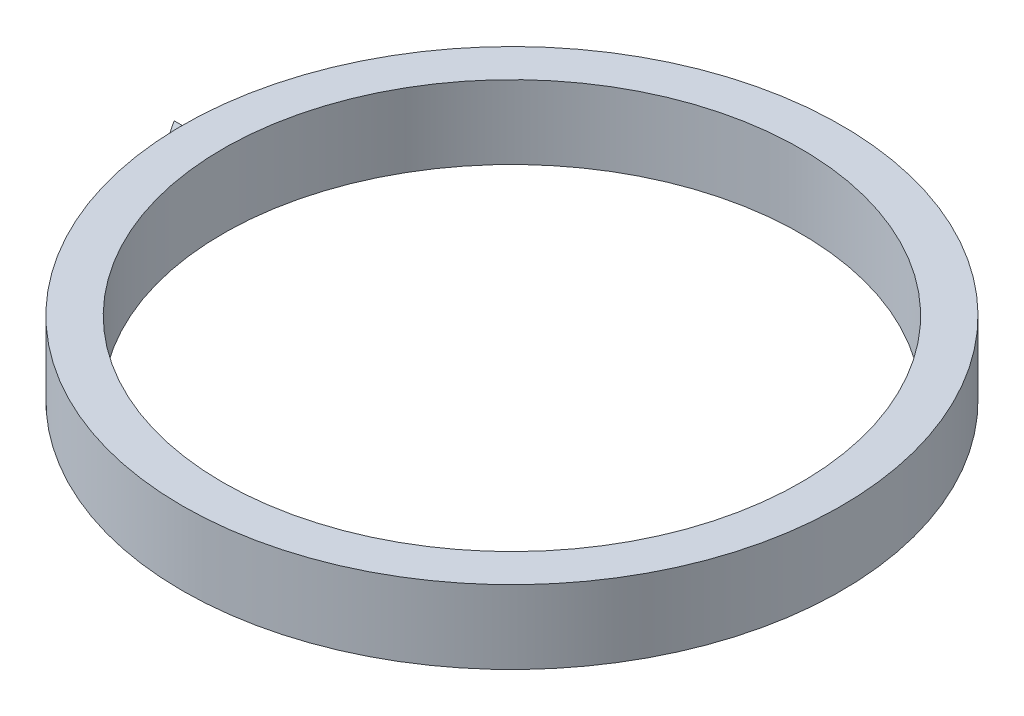
SolidWorks part; units mm, degrees
ref_plane "Front Plane" through (0, 0, 0) normal (0, 0, 1) x (1, 0, 0)
ref_plane "Top Plane" through (0, 0, 0) normal (0, 1, 0) x (1, 0, 0)
ref_plane "Right Plane" through (0, 0, 0) normal (1, 0, 0) x (0, 0, -1)
sketch "Sketch1" plane through (0, 0, 0) normal (0, 1, 0) x (1, 0, 0)
  circle A0 centre (0, 0) radius 19.5
  circle A1 centre (0, 0) radius 17.1
  dimension "D1" = 39
  dimension "D2" = 34.2
extrude "Boss-Extrude1" add sketch "Sketch1" along normal blind 4.3478
ref_plane "Plane1" through (-19.5, 0, 0) normal (-1, 0, 0) x (0, 0, 1)
sketch "Sketch2" plane through (-19.5, 0, 0) normal (-1, 0, 0) x (0, 0, 1)
  line L2 (0, 0.0093) -> (-1.087, 2.1739)
  line L3 (1.087, 2.1739) -> (0, 0.0093)
  line L4 (0, 4.3385) -> (-1.087, 2.1739)
  line L5 (1.087, 2.1739) -> (0, 4.3385)
  point P9 (0, 2.1739)
  point P12 (0, 2.1739)
extrude "Boss-Extrude2" add sketch "Sketch2" along normal mid plane 2.1739
chamfer "Chamfer1" distance 0.6 distance2 0.971 4 edges at (-20.587, 3.2562, 0.5435) (-20.587, 1.0916, 0.5435) (-20.587, 1.0916, -0.5435) (-20.587, 3.2562, -0.5435)
equation "\"clearance\"= 0.3mm ' Freely and easily sliding. Used as a gap between the telescopic sections."
equation "\"clearance2\" = 0.1mm ' Used as a gap between rings next to each other."
equation "\"interference\"= 0.1mm ' This is like clearance1 but when two parts should just fit together rather than freely spin."
equation "\"D2@Sketch1\"=34.00mm+\"interference\" * 2"
